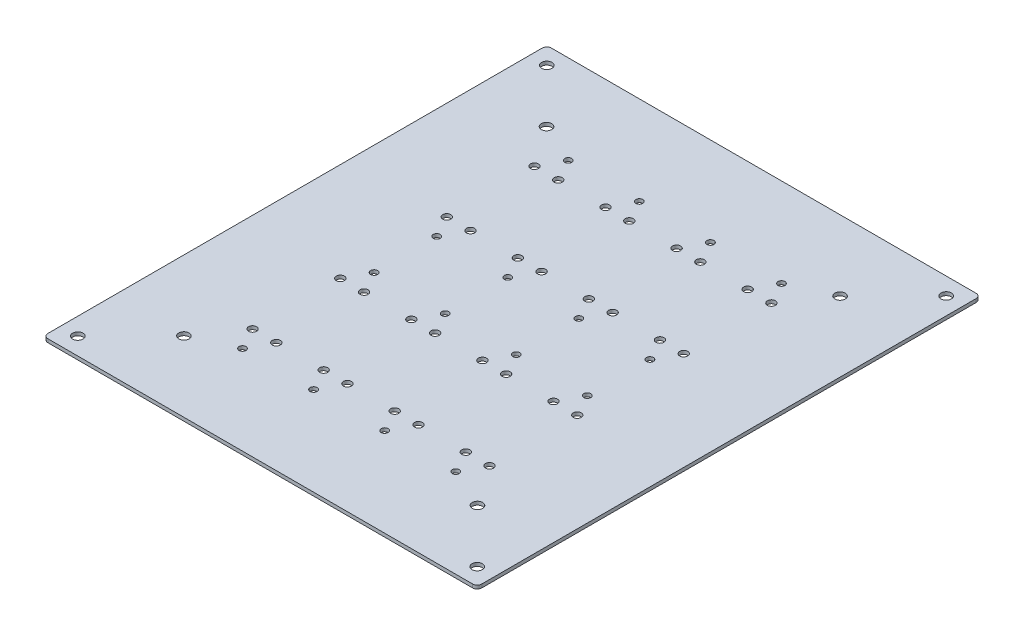
SolidWorks part; units mm, degrees
ref_plane "Front Plane" through (0, 0, 0) normal (0, 0, 1) x (1, 0, 0)
ref_plane "Top Plane" through (0, 0, 0) normal (0, 1, 0) x (1, 0, 0)
ref_plane "Right Plane" through (0, 0, 0) normal (1, 0, 0) x (0, 0, -1)
sketch "Sketch1" plane through (0, 0, 0) normal (0, 1, 0) x (1, 0, 0)
  line L0 (0, 109.35) -> (0, -109.35) construction
  line L1 (-94.24, 109.35) -> (94.24, 109.35)
  line L2 (-94.24, 109.35) -> (-94.24, -109.35)
  line L3 (-94.24, -109.35) -> (94.24, -109.35)
  line L4 (94.24, 109.35) -> (94.24, -109.35)
  line L5 (-94.24, 109.35) -> (94.24, -109.35) construction
  line L6 (-94.24, -109.35) -> (94.24, 109.35) construction
  line L7 (94.24, 0) -> (-94.24, 0) construction
  point P0 (0, 0)
  dimension "D1" = 218.7
  dimension "D2" = 188.48
extrude "Boss-Extrude1" add sketch "Sketch1" along normal mid plane 1.5
sketch "Sketch2" plane through (0, 0.75, 0) normal (0, 1, 0) x (1, 0, 0)
  line L0 (-46.305, 61.225) -> (-46.305, 23.125) construction
  line L1 (-51.46, 42.175) -> (-41.15, 42.175) construction
  line L2 (-51.46, 23.125) -> (-41.15, 23.125) construction
  line L3 (-51.46, 61.225) -> (-41.15, 61.225) construction
  line L4 (-46.305, 70.75) -> (-46.305, 61.225) construction
  line L5 (-46.305, 23.125) -> (-46.305, 13.6) construction
  line L6 (-7.5, 69.35) -> (7.5, 69.35) construction
  line L7 (0, 126.4554) -> (0, 12.2446) construction
  line L8 (-54.24, 69.35) -> (-38.37, 69.35) construction
  line L9 (-38.37, 69.35) -> (-38.37, 15) construction
  line L10 (-38.37, 15) -> (-54.24, 15) construction
  line L11 (-54.24, 15) -> (-54.24, 69.35) construction
  line L12 (-94.24, 109.35) -> (-94.24, -109.35) construction
  line L13 (94.24, 109.35) -> (-94.24, 109.35) construction
  line L14 (-15.435, 61.225) -> (-15.435, 23.125) construction
  line L15 (-20.59, 42.175) -> (-10.28, 42.175) construction
  line L16 (-20.59, 23.125) -> (-10.28, 23.125) construction
  line L17 (-20.59, 61.225) -> (-10.28, 61.225) construction
  line L18 (-15.435, 70.75) -> (-15.435, 61.225) construction
  line L19 (-15.435, 23.125) -> (-15.435, 13.6) construction
  line L20 (-23.37, 69.35) -> (-7.5, 69.35) construction
  line L21 (-7.5, 69.35) -> (-7.5, 15) construction
  line L22 (-7.5, 15) -> (-23.37, 15) construction
  line L23 (-23.37, 15) -> (-23.37, 69.35) construction
  line L24 (15.435, 61.225) -> (15.435, 23.125) construction
  line L25 (10.28, 42.175) -> (20.59, 42.175) construction
  line L26 (10.28, 23.125) -> (20.59, 23.125) construction
  line L27 (10.28, 61.225) -> (20.59, 61.225) construction
  line L28 (15.435, 70.75) -> (15.435, 61.225) construction
  line L29 (15.435, 23.125) -> (15.435, 13.6) construction
  line L30 (7.5, 69.35) -> (23.37, 69.35) construction
  line L31 (23.37, 69.35) -> (23.37, 15) construction
  line L32 (23.37, 15) -> (7.5, 15) construction
  line L33 (7.5, 15) -> (7.5, 69.35) construction
  line L34 (46.305, 61.225) -> (46.305, 23.125) construction
  line L35 (41.15, 42.175) -> (51.46, 42.175) construction
  line L36 (41.15, 23.125) -> (51.46, 23.125) construction
  line L37 (41.15, 61.225) -> (51.46, 61.225) construction
  line L38 (46.305, 70.75) -> (46.305, 61.225) construction
  line L39 (46.305, 23.125) -> (46.305, 13.6) construction
  line L40 (38.37, 69.35) -> (54.24, 69.35) construction
  line L41 (54.24, 69.35) -> (54.24, 15) construction
  line L42 (54.24, 15) -> (38.37, 15) construction
  line L43 (38.37, 15) -> (38.37, 69.35) construction
  line L44 (-94.24, 0) -> (94.24, 0) construction
  line L45 (94.24, -109.35) -> (94.24, 109.35) construction
  line L46 (38.37, -15) -> (38.37, -69.35) construction
  line L47 (54.24, -15) -> (38.37, -15) construction
  line L48 (54.24, -69.35) -> (54.24, -15) construction
  line L49 (38.37, -69.35) -> (54.24, -69.35) construction
  line L50 (46.305, -23.125) -> (46.305, -13.6) construction
  line L51 (46.305, -70.75) -> (46.305, -61.225) construction
  line L52 (41.15, -61.225) -> (51.46, -61.225) construction
  line L53 (41.15, -23.125) -> (51.46, -23.125) construction
  line L54 (41.15, -42.175) -> (51.46, -42.175) construction
  line L55 (46.305, -61.225) -> (46.305, -23.125) construction
  line L56 (7.5, -15) -> (7.5, -69.35) construction
  line L57 (23.37, -15) -> (7.5, -15) construction
  line L58 (23.37, -69.35) -> (23.37, -15) construction
  line L59 (7.5, -69.35) -> (23.37, -69.35) construction
  line L60 (15.435, -23.125) -> (15.435, -13.6) construction
  line L61 (15.435, -70.75) -> (15.435, -61.225) construction
  line L62 (10.28, -61.225) -> (20.59, -61.225) construction
  line L63 (10.28, -23.125) -> (20.59, -23.125) construction
  line L64 (10.28, -42.175) -> (20.59, -42.175) construction
  line L65 (15.435, -61.225) -> (15.435, -23.125) construction
  line L66 (-23.37, -15) -> (-23.37, -69.35) construction
  line L67 (-7.5, -15) -> (-23.37, -15) construction
  line L68 (-7.5, -69.35) -> (-7.5, -15) construction
  line L69 (-23.37, -69.35) -> (-7.5, -69.35) construction
  line L70 (-15.435, -23.125) -> (-15.435, -13.6) construction
  line L71 (-15.435, -70.75) -> (-15.435, -61.225) construction
  line L72 (-20.59, -61.225) -> (-10.28, -61.225) construction
  line L73 (-20.59, -23.125) -> (-10.28, -23.125) construction
  line L74 (-20.59, -42.175) -> (-10.28, -42.175) construction
  line L75 (-15.435, -61.225) -> (-15.435, -23.125) construction
  line L76 (-54.24, -15) -> (-54.24, -69.35) construction
  line L77 (-38.37, -15) -> (-54.24, -15) construction
  line L78 (-38.37, -69.35) -> (-38.37, -15) construction
  line L79 (-54.24, -69.35) -> (-38.37, -69.35) construction
  line L80 (-46.305, -23.125) -> (-46.305, -13.6) construction
  line L81 (-46.305, -70.75) -> (-46.305, -61.225) construction
  line L82 (-51.46, -61.225) -> (-41.15, -61.225) construction
  line L83 (-51.46, -23.125) -> (-41.15, -23.125) construction
  line L84 (-51.46, -42.175) -> (-41.15, -42.175) construction
  line L85 (-46.305, -61.225) -> (-46.305, -23.125) construction
  circle A0 centre (-41.15, 61.225) radius 1.75
  circle A1 centre (-51.46, 61.225) radius 1.75
  circle A2 centre (-51.46, 23.125) radius 1.75
  circle A3 centre (-41.15, 23.125) radius 1.75
  circle A4 centre (-46.305, 70.75) radius 1.5
  circle A5 centre (-46.305, 13.6) radius 1.5
  circle A6 centre (-10.28, 61.225) radius 1.75
  circle A7 centre (-20.59, 61.225) radius 1.75
  circle A8 centre (-20.59, 23.125) radius 1.75
  circle A9 centre (-10.28, 23.125) radius 1.75
  circle A10 centre (-15.435, 70.75) radius 1.5
  circle A11 centre (-15.435, 13.6) radius 1.5
  circle A12 centre (20.59, 61.225) radius 1.75
  circle A13 centre (10.28, 61.225) radius 1.75
  circle A14 centre (10.28, 23.125) radius 1.75
  circle A15 centre (20.59, 23.125) radius 1.75
  circle A16 centre (15.435, 70.75) radius 1.5
  circle A17 centre (15.435, 13.6) radius 1.5
  circle A18 centre (51.46, 61.225) radius 1.75
  circle A19 centre (41.15, 61.225) radius 1.75
  circle A20 centre (41.15, 23.125) radius 1.75
  circle A21 centre (51.46, 23.125) radius 1.75
  circle A22 centre (46.305, 70.75) radius 1.5
  circle A23 centre (46.305, 13.6) radius 1.5
  circle A24 centre (46.305, -13.6) radius 1.5
  circle A25 centre (46.305, -70.75) radius 1.5
  circle A26 centre (51.46, -23.125) radius 1.75
  circle A27 centre (41.15, -23.125) radius 1.75
  circle A28 centre (41.15, -61.225) radius 1.75
  circle A29 centre (51.46, -61.225) radius 1.75
  circle A30 centre (15.435, -13.6) radius 1.5
  circle A31 centre (15.435, -70.75) radius 1.5
  circle A32 centre (20.59, -23.125) radius 1.75
  circle A33 centre (10.28, -23.125) radius 1.75
  circle A34 centre (10.28, -61.225) radius 1.75
  circle A35 centre (20.59, -61.225) radius 1.75
  circle A36 centre (-15.435, -13.6) radius 1.5
  circle A37 centre (-15.435, -70.75) radius 1.5
  circle A38 centre (-10.28, -23.125) radius 1.75
  circle A39 centre (-20.59, -23.125) radius 1.75
  circle A40 centre (-20.59, -61.225) radius 1.75
  circle A41 centre (-10.28, -61.225) radius 1.75
  circle A42 centre (-46.305, -13.6) radius 1.5
  circle A43 centre (-46.305, -70.75) radius 1.5
  circle A44 centre (-41.15, -23.125) radius 1.75
  circle A45 centre (-51.46, -23.125) radius 1.75
  circle A46 centre (-51.46, -61.225) radius 1.75
  circle A47 centre (-41.15, -61.225) radius 1.75
  point P4 (-46.305, 42.175)
  point P175 (0, 69.35)
  dimension "D1" = 3.5
  dimension "D5" = 3
  dimension "D2" = 38.1
  dimension "D3" = 10.31
  dimension "D4" = 57.15
  dimension "D7" = 40
  dimension "D8" = 54.35
  dimension "D9" = 1.4
  dimension "D10" = 15.87
  dimension "D11" = 2.78
  dimension "D13" = 15
  dimension "D14" = 15
  dimension "D12" = 4
extrude "Cut-Extrude1" cut sketch "Sketch2" against normal through all both and the other way through all
fillet "Fillet1" radius 2 1 edges at (-94.24, 0, -109.35)
fillet "Fillet2" radius 2 1 edges at (-94.24, 0, 109.35)
fillet "Fillet3" radius 2 1 edges at (94.24, 0, 109.35)
fillet "Fillet4" radius 2 1 edges at (94.24, 0, -109.35)
sketch "Sketch3" plane through (0, 0.75, 0) normal (0, 1, 0) x (1, 0, 0)
  line L0 (-86.74, 101.85) -> (-86.74, -101.85) construction
  line L1 (-86.74, -101.85) -> (86.74, -101.85) construction
  line L2 (86.74, -101.85) -> (86.74, 101.85) construction
  line L3 (86.74, 101.85) -> (-86.74, 101.85) construction
  line L4 (92.24, 109.35) -> (-92.24, 109.35) construction
  line L5 (-94.24, 107.35) -> (-94.24, -107.35) construction
  line L6 (-92.24, -109.35) -> (92.24, -109.35) construction
  line L7 (94.24, -107.35) -> (94.24, 107.35) construction
  line L10 (-63.75, 78.75) -> (63.75, 78.75) construction
  line L11 (-63.75, 78.75) -> (-63.75, -78.75) construction
  line L13 (-63.75, -78.75) -> (63.75, -78.75) construction
  line L14 (63.75, -78.75) -> (63.75, 78.75) construction
  circle A0 centre (-86.74, 101.85) radius 2.25
  circle A1 centre (86.74, 101.85) radius 2.25
  circle A2 centre (86.74, -101.85) radius 2.25
  circle A3 centre (-86.74, -101.85) radius 2.25
  circle A4 centre (-63.75, 78.75) radius 2.25
  circle A5 centre (63.75, 78.75) radius 2.25
  circle A6 centre (63.75, -78.75) radius 2.25
  circle A7 centre (-63.75, -78.75) radius 2.25
  dimension "D1" = 4.5
  dimension "D6" = 4.5
  dimension "D2" = 7.5
  dimension "D3" = 7.5
  dimension "D4" = 7.5
  dimension "D5" = 7.5
  dimension "D7" = 30.49
  dimension "D8" = 30.6
  dimension "D9" = 30.49
  dimension "D10" = 30.6
extrude "Cut-Extrude2" cut sketch "Sketch3" against normal through all both and the other way through all
